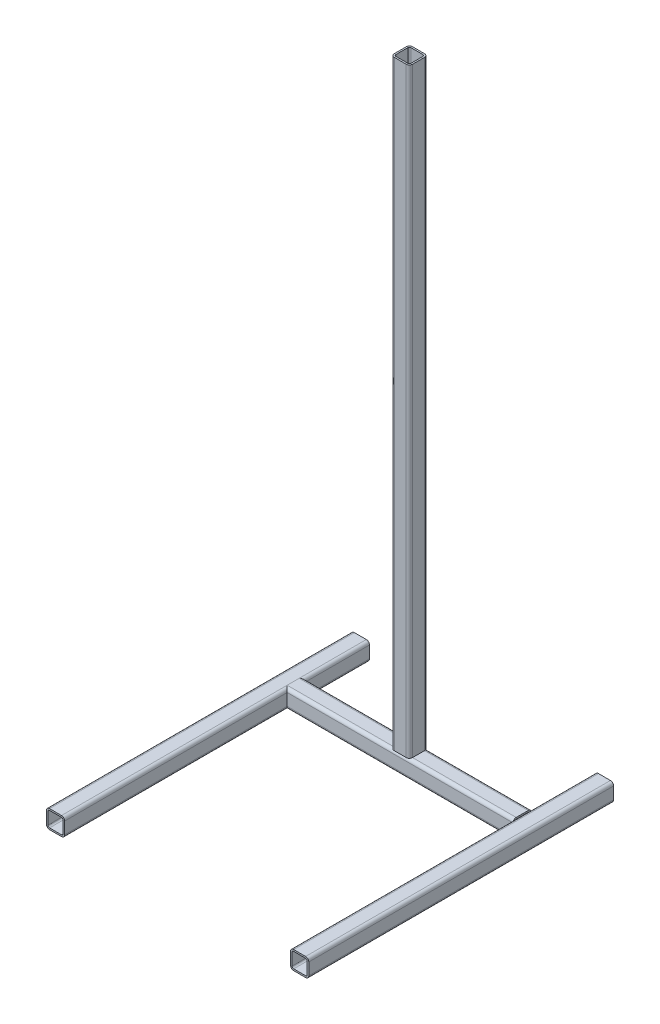
SolidWorks part; units mm, degrees
ref_plane "Plano frontal" through (0, 0, 0) normal (0, 0, 1) x (1, 0, 0)
ref_plane "Plano superior" through (0, 0, 0) normal (0, 1, 0) x (1, 0, 0)
ref_plane "Plano direito" through (0, 0, 0) normal (1, 0, 0) x (0, 0, -1)
sketch3d "3DSketch2"
  line L0 (0, 0, 0) -> (0, 1000, 0)
  line L1 (200, 0, -120) -> (200, 0, 380) construction
  line L2 (-200, 0, 0) -> (200, 0, 0)
  line L3 (200, 0, 0) -> (200, 0, 380) construction
  line L4 (200, 0, 0) -> (200, 0, -120) construction
  line L7 (-200, 0, 0) -> (200, 0, 0) construction
  line L8 (-200.454, 0, 380) -> (-200.454, 0, -120)
  line L9 (200, 0, 380) -> (200, 0, -120)
  dimension "D1" = 500
  dimension "D2" = 120
  dimension "D3" = 1000
  dimension "D4" = 400
  dimension "D5" = 120
other "Componente estrutural1"
ref_plane "Plano6" through (0, 0, 0) normal (0, 1, 0) x (1, 0, 0)
sketch "Sketch1" plane through (0, 0, 0) normal (0, 1, 0) x (1, 0, 0)
  line L0 (-9.8, -12.4) -> (9.8, -12.4)
  line L1 (-12.4, -9.8) -> (-12.4, 9.8)
  line L2 (9.8, 12.4) -> (-9.8, 12.4)
  line L3 (12.4, 9.8) -> (12.4, -9.8)
  line L4 (-9.8, -15) -> (9.8, -15)
  line L5 (-15, -9.8) -> (-15, 9.8)
  line L6 (9.8, 15) -> (-9.8, 15)
  line L7 (15, 9.8) -> (15, -9.8)
  arc A0 (15, 9.8) -> (9.8, 15) centre (9.8, 9.8) ccw
  arc A1 (9.8, -15) -> (15, -9.8) centre (9.8, -9.8) ccw
  arc A2 (-15, -9.8) -> (-9.8, -15) centre (-9.8, -9.8) ccw
  arc A3 (-9.8, 15) -> (-15, 9.8) centre (-9.8, 9.8) ccw
  arc A4 (-9.8, 12.4) -> (-12.4, 9.8) centre (-9.8, 9.8) ccw
  arc A5 (12.4, 9.8) -> (9.8, 12.4) centre (9.8, 9.8) ccw
  arc A6 (9.8, -12.4) -> (12.4, -9.8) centre (9.8, -9.8) ccw
  arc A7 (-12.4, -9.8) -> (-9.8, -12.4) centre (-9.8, -9.8) ccw
  point P0 (-15, 0)
  point P1 (15, 0)
  point P2 (0, 15)
  point P3 (0, -15)
  point P4 (0, 0)
  point P5 (-15, -15)
  point P6 (15, -15)
  point P7 (15, 15)
  point P8 (-15, 15)
  point P33 (0, 0)
  dimension "D1" = 5.2
  dimension "Thickness" = 2.6
  dimension "V_leg" = 30
